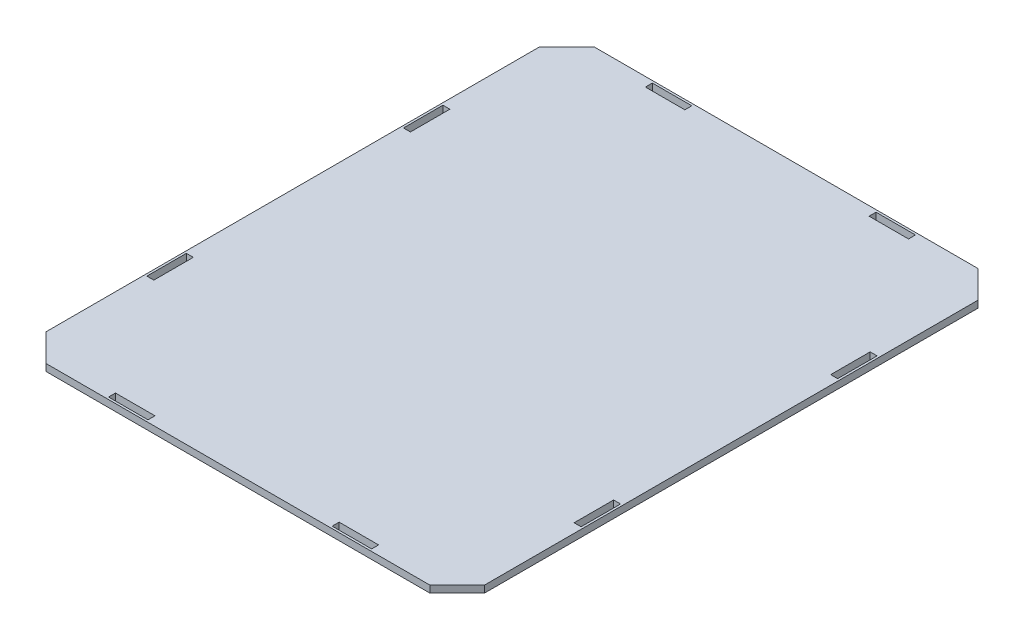
SolidWorks part; units mm, degrees
ref_plane "Front Plane" through (0, 0, 0) normal (0, 0, 1) x (1, 0, 0)
ref_plane "Top Plane" through (0, 0, 0) normal (0, 1, 0) x (1, 0, 0)
ref_plane "Right Plane" through (0, 0, 0) normal (1, 0, 0) x (0, 0, -1)
sketch "Sketch2" plane through (0, 0, 0) normal (0, 1, 0) x (1, 0, 0)
  line L1 (-200, -250) -> (200, -250)
  line L2 (-200, -250) -> (-200, 250)
  line L3 (-200, 250) -> (200, 250)
  line L4 (200, -250) -> (200, 250)
  line L5 (-200, -250) -> (200, 250) construction
  line L6 (-200, 250) -> (200, -250) construction
  point P0 (0, 0)
  dimension "D1" = 400
  dimension "D2" = 500
extrude "Boss-Extrude2" add sketch "Sketch2" along normal blind 6.35
sketch "Sketch3" plane through (0, 6.35, 0) normal (0, 1, 0) x (1, 0, 0)
  line L0 (-139.5, 250) -> (-139.5, -250) construction
  line L1 (200, 250) -> (-200, 250) construction
  line L2 (-200, -250) -> (200, -250) construction
  line L3 (-200, 175) -> (200, 175) construction
  line L4 (-200, 250) -> (-200, -250) construction
  line L5 (200, -250) -> (200, 250) construction
  line L6 (-200, 0) -> (200, 0) construction
  line L7 (0, 250) -> (0, -250) construction
  line L8 (139.5, 250) -> (139.5, -250) construction
  line L9 (-200, -175) -> (200, -175) construction
  circle A0 centre (-139.5, 175) radius 7.6335
  circle A2 centre (139.5, -175) radius 3.266
  circle A4 centre (139.5, 175) radius 10.436
  circle A5 centre (-139.5, -175) radius 13.4263
  dimension "D1" = 139.5
  dimension "D2" = 175
chamfer "Chamfer1" distance 25 angle 45 4 edges at (-200, 3.175, -250) (200, 3.175, -250) (-200, 3.175, 250) (200, 3.175, 250)
sketch "Sketch9" plane through (0, 6.35, 0) normal (0, 1, 0) x (1, 0, 0)
  line L0 (-187.5, -248) -> (198, -248) construction
  line L1 (198, 135) -> (191.65, 135)
  line L2 (191.65, 99) -> (191.65, 135)
  line L3 (198, -248) -> (198, 223.0086) construction
  line L4 (198, 99) -> (191.65, 99)
  line L5 (-175, -250) -> (175, -250) construction
  line L6 (-120, -250) -> (-120, -216.1128) construction
  line L7 (0, -250) -> (0, -204.2707) construction
  line L8 (0, 250) -> (0, -250) construction
  line L9 (120, -241.65) -> (84, -241.65)
  line L10 (-120, -248) -> (-84, -248)
  line L11 (-120, -248) -> (-120, -241.65)
  line L12 (-120, -241.65) -> (-84, -241.65)
  line L13 (-84, -248) -> (-84, -241.65)
  line L14 (84, -248) -> (84, -241.65)
  line L15 (120, -248) -> (84, -248)
  line L16 (120, -248) -> (120, -241.65)
  line L17 (-200, 0) -> (200, 0) construction
  line L18 (-120, 241.65) -> (-84, 241.65)
  line L19 (-84, 248) -> (-84, 241.65)
  line L20 (-120, 248) -> (-84, 248)
  line L21 (-120, 248) -> (-120, 241.65)
  line L22 (120, 248) -> (120, 241.65)
  line L23 (120, 248) -> (84, 248)
  line L24 (84, 248) -> (84, 241.65)
  line L25 (120, 241.65) -> (84, 241.65)
  line L26 (200, -135) -> (111.3102, -135) construction
  line L27 (200, -225) -> (200, 225) construction
  line L28 (198, 99) -> (198, 135)
  line L29 (198, -99) -> (191.65, -99)
  line L30 (198, -99) -> (198, -135)
  line L31 (198, -135) -> (191.65, -135)
  line L32 (191.65, -99) -> (191.65, -135)
  line L33 (0, 250) -> (0, -250) construction
  line L34 (-198, -135) -> (-191.65, -135)
  line L35 (-191.65, -99) -> (-191.65, -135)
  line L36 (-198, -99) -> (-191.65, -99)
  line L37 (-198, -99) -> (-198, -135)
  line L38 (-198, 99) -> (-198, 135)
  line L39 (-198, 99) -> (-191.65, 99)
  line L40 (-191.65, 99) -> (-191.65, 135)
  line L41 (-198, 135) -> (-191.65, 135)
  dimension "D1" = 2
  dimension "D2" = 120
  dimension "D3" = 6.35
  dimension "D4" = 36
  dimension "D5" = 135
  dimension "D6" = 6.35
  dimension "D7" = 36
  dimension "D8" = 2
extrude "Cut-Extrude1" cut sketch "Sketch9" against normal through all
